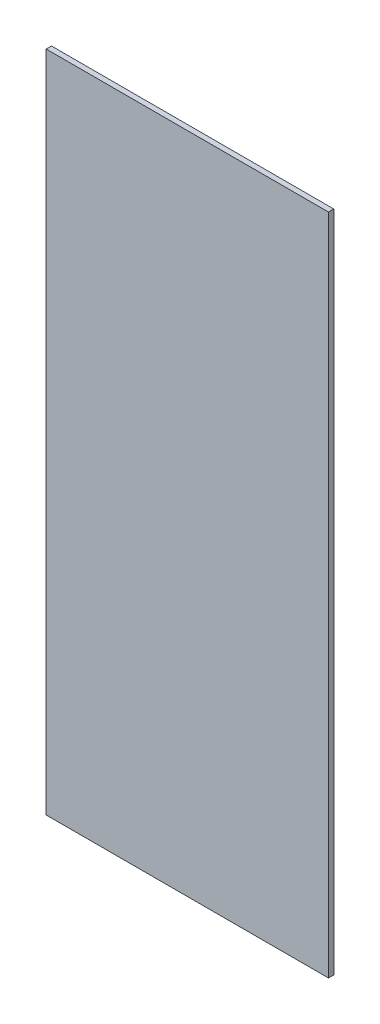
SolidWorks part; units mm, degrees
ref_plane "Plan de face" through (0, 0, 0) normal (0, 0, 1) x (1, 0, 0)
ref_plane "Plan de dessus" through (0, 0, 0) normal (0, 1, 0) x (1, 0, 0)
ref_plane "Plan de droite" through (0, 0, 0) normal (1, 0, 0) x (0, 0, -1)
sketch "Esquisse1" plane through (0, 0, 0) normal (0, 0, 1) x (1, 0, 0)
  line L1 (-160, -376) -> (160, -376)
  line L2 (-160, -376) -> (-160, 376)
  line L3 (-160, 376) -> (160, 376)
  line L4 (160, -376) -> (160, 376)
  line L5 (-160, -376) -> (160, 376) construction
  line L6 (-160, 376) -> (160, -376) construction
  point P0 (0, 0)
  dimension "D1" = 320
  dimension "D2" = 752
extrude "Boss.-Extru.1" add sketch "Esquisse1" along normal blind 6
